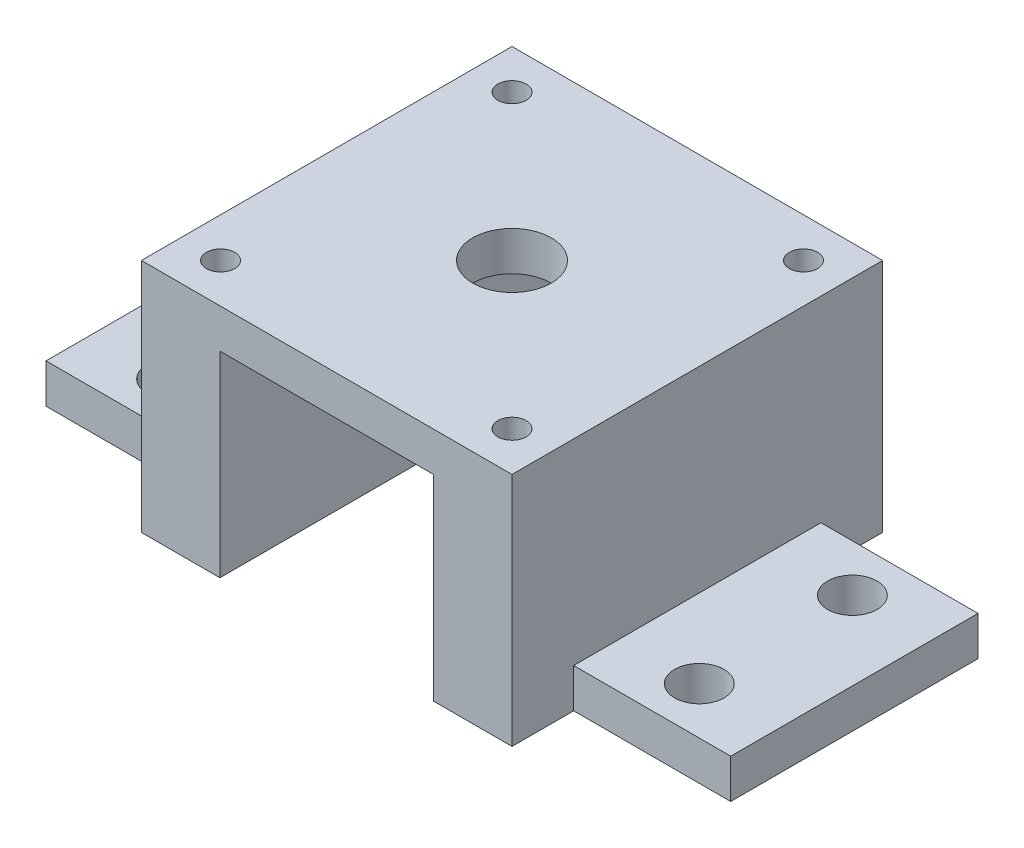
SolidWorks part; units mm, degrees
material "6061-T6 (SS)"
ref_plane "Front Plane" through (0, 0, 0) normal (0, 0, 1) x (1, 0, 0)
ref_plane "Top Plane" through (0, 0, 0) normal (0, 1, 0) x (1, 0, 0)
ref_plane "Right Plane" through (0, 0, 0) normal (1, 0, 0) x (0, 0, -1)
sketch "Sketch1" plane through (0, 0, 0) normal (0, 1, 0) x (1, 0, 0)
  line L1 (-59.944, 25.0118) -> (0, 25.0118)
  line L2 (-59.944, 25.0118) -> (-59.944, -34.9322)
  line L3 (-59.944, -34.9322) -> (0, -34.9322)
  line L4 (0, 25.0118) -> (0, -34.9322)
  dimension "D1" = 59.944
extrude "Boss-Extrude1" add sketch "Sketch1" along normal blind 38.1 contours L1 L4 L3 L2
sketch "Sketch2" plane through (0, 0, 34.9322) normal (0, 0, 1) x (1, 0, 0)
  line L0 (-59.944, 0) -> (0, 0) construction
  line L1 (-47.244, 0) -> (-12.7, 0)
  line L2 (-47.244, 0) -> (-47.244, 31.75)
  line L3 (-47.244, 31.75) -> (-12.7, 31.75)
  line L4 (-12.7, 0) -> (-12.7, 31.75)
  line L5 (-59.944, 38.1) -> (0, 38.1) construction
  line L6 (-59.944, 38.1) -> (-59.944, 0) construction
  line L7 (0, 38.1) -> (0, 0) construction
  dimension "D1" = 6.35
  dimension "D2" = 12.7
  dimension "D3" = 12.7
extrude "Cut-Extrude1" cut sketch "Sketch2" against normal through all
sketch "Sketch3" plane through (0, 38.1, 0) normal (0, 1, 0) x (1, 0, 0)
  line L0 (-59.944, 25.0118) -> (-59.944, -34.9322) construction
  line L2 (-59.944, -34.9322) -> (0, -34.9322) construction
  circle A0 centre (-29.972, -4.9602) radius 6.35
  dimension "D3" = 12.7
  dimension "D1" = 29.972
  dimension "D2" = 29.972
extrude "Cut-Extrude2" cut sketch "Sketch3" against normal through all
sketch "Sketch4" plane through (0, 0, 0) normal (1, 0, 0) x (0, 0, -1)
  line L0 (25.0118, 0) -> (-34.9322, 0) construction
  line L1 (-24.9602, 0) -> (15.0398, 0)
  line L2 (-24.9602, 0) -> (-24.9602, 6.35)
  line L3 (-24.9602, 6.35) -> (15.0398, 6.35)
  line L4 (15.0398, 0) -> (15.0398, 6.35)
  line L5 (-34.9322, 38.1) -> (-34.9322, 0) construction
  dimension "D1" = 40
  dimension "D2" = 9.972
  dimension "D3" = 6.35
extrude "Boss-Extrude2" add sketch "Sketch4" along normal blind 25.4
sketch "Sketch5" plane through (-59.944, 0, 0) normal (-1, 0, 0) x (0, 0, 1)
  line L1 (-15.0398, 0) -> (24.9602, 0)
  line L2 (-15.0398, 0) -> (-15.0398, 6.35)
  line L3 (-15.0398, 6.35) -> (24.9602, 6.35)
  line L4 (24.9602, 0) -> (24.9602, 6.35)
  dimension "D1" = 40
  dimension "D2" = 6.35
extrude "Boss-Extrude3" add sketch "Sketch5" along normal blind 25.4
sketch "Sketch6" plane through (0, 6.35, 0) normal (0, 1, 0) x (1, 0, 0)
  line L0 (-85.344, -24.9602) -> (-85.344, 15.0398) construction
  line L1 (-85.344, 15.0398) -> (-59.944, 15.0398) construction
  line L2 (-85.344, -24.9602) -> (-59.944, -24.9602) construction
  line L3 (25.4, -24.9602) -> (0, -24.9602) construction
  line L4 (25.4, 15.0398) -> (0, 15.0398) construction
  line L5 (25.4, 15.0398) -> (25.4, -24.9602) construction
  circle A0 centre (-72.644, 7.4198) radius 4
  circle A1 centre (-72.644, -17.3402) radius 4
  circle A2 centre (12.7, 7.4198) radius 4
  circle A3 centre (12.7, -17.3402) radius 4
  dimension "D5" = 8
  dimension "D1" = 12.7
  dimension "D2" = 12.7
  dimension "D3" = 7.62
  dimension "D4" = 7.62
  dimension "D6" = 7.62
  dimension "D7" = 7.62
  dimension "D8" = 12.7
  dimension "D9" = 12.7
extrude "Cut-Extrude3" cut sketch "Sketch6" against normal through all
sketch "Sketch7" plane through (0, 38.1, 0) normal (0, 1, 0) x (1, 0, 0)
  line L0 (-59.944, 25.0118) -> (-59.944, -34.9322) construction
  line L1 (-59.944, 25.0118) -> (0, 25.0118) construction
  line L2 (-53.5432, 18.611) -> (-53.5432, -34.9322) construction
  line L3 (-59.944, -34.9322) -> (0, -34.9322) construction
  line L4 (-53.5432, 18.611) -> (0, 18.611) construction
  line L5 (0, 25.0118) -> (0, -34.9322) construction
  line L6 (-6.4008, -28.5314) -> (-6.4008, 25.0118) construction
  line L7 (-6.4008, -28.5314) -> (-59.944, -28.5314) construction
  circle A0 centre (-53.5432, 18.611) radius 2.286
  circle A1 centre (-6.4008, -28.5314) radius 2.286
  circle A2 centre (-53.5432, -28.5314) radius 2.286
  circle A3 centre (-6.4008, 18.611) radius 2.286
  dimension "D1" = 4.572
  dimension "D2" = 6.4008
  dimension "D3" = 6.4008
  dimension "D4" = 6.4008
  dimension "D5" = 6.4008
extrude "Cut-Extrude4" cut sketch "Sketch7" against normal blind 12.7
equation "\"D2@Sketch4\"=(2.36in/2)-20mm"
